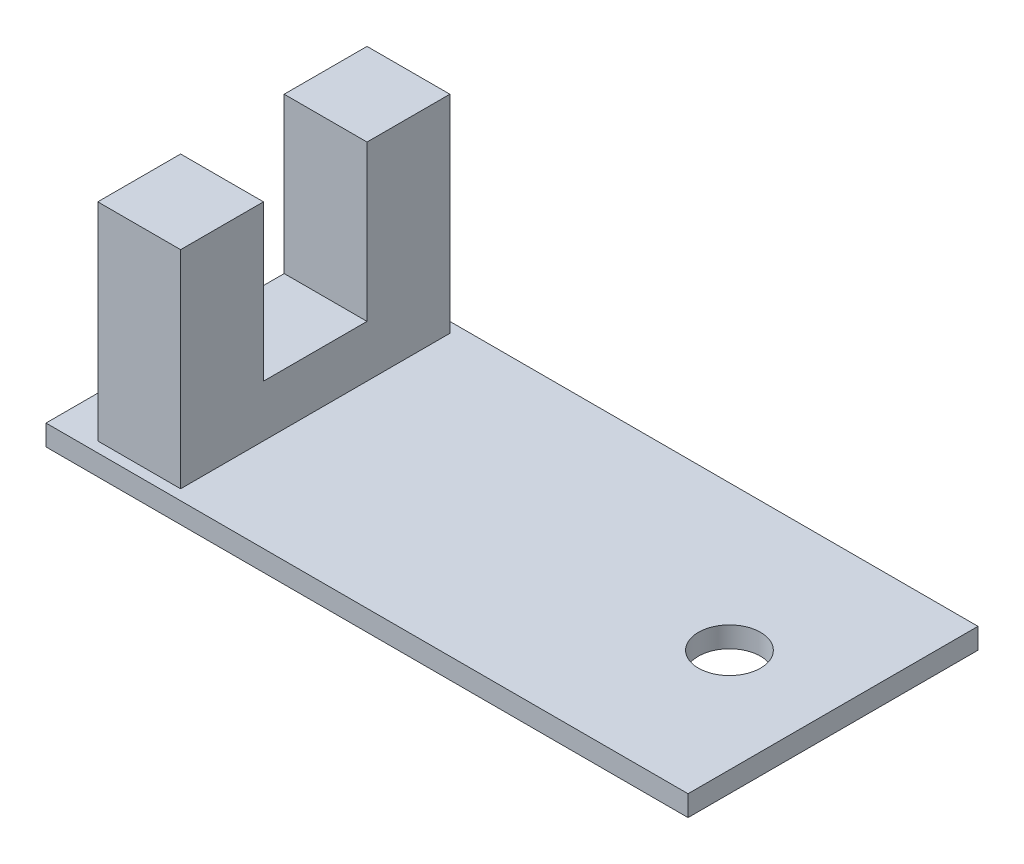
SolidWorks part; units mm, degrees
ref_plane "Front Plane" through (0, 0, 0) normal (0, 0, 1) x (1, 0, 0)
ref_plane "Top Plane" through (0, 0, 0) normal (0, 1, 0) x (1, 0, 0)
ref_plane "Right Plane" through (0, 0, 0) normal (1, 0, 0) x (0, 0, -1)
sketch "Sketch1" plane through (0, 0, 0) normal (0, 1, 0) x (1, 0, 0)
  line L1 (0, 0) -> (31, 0)
  line L2 (0, 0) -> (0, -14)
  line L3 (0, -14) -> (31, -14)
  line L4 (31, 0) -> (31, -14)
  dimension "D1" = 31
  dimension "D2" = 14
extrude "Boss-Extrude1" add sketch "Sketch1" along normal blind 1
sketch "Sketch2" plane through (0, 1, 0) normal (0, 1, 0) x (1, 0, 0)
  line L0 (0, -14) -> (31, -14) construction
  line L1 (2, -13.5) -> (6, -13.5)
  line L2 (2, -13.5) -> (2, -9.5)
  line L3 (2, -9.5) -> (6, -9.5)
  line L4 (6, -13.5) -> (6, -9.5)
  line L5 (2, -4.5) -> (6, -4.5)
  line L6 (2, -4.5) -> (2, -0.5)
  line L7 (2, -0.5) -> (6, -0.5)
  line L8 (6, -4.5) -> (6, -0.5)
  line L9 (0, 0) -> (0, -14) construction
  dimension "D1" = 5
  dimension "D2" = 4
  dimension "D3" = 4
  dimension "D4" = 0.5
  dimension "D5" = 4
  dimension "D6" = 4
  dimension "D7" = 2
  dimension "D8" = 2
extrude "Boss-Extrude2" add sketch "Sketch2" along normal blind 10
sketch "Sketch3" plane through (0, 1, 0) normal (0, 1, 0) x (1, 0, 0)
  line L0 (31, -14) -> (31, 0) construction
  circle A0 centre (26, -7) radius 1.5
  dimension "D1" = 3
  dimension "D2" = 5
extrude "Cut-Extrude1" cut sketch "Sketch3" against normal through all
sketch "Sketch4" plane through (0, 1, 0) normal (0, 1, 0) x (1, 0, 0)
  line L1 (2, -4.5) -> (6, -4.5)
  line L2 (2, -4.5) -> (2, -9.5)
  line L3 (2, -9.5) -> (6, -9.5)
  line L4 (6, -4.5) -> (6, -9.5)
extrude "Boss-Extrude3" add sketch "Sketch4" along normal blind 2.5
